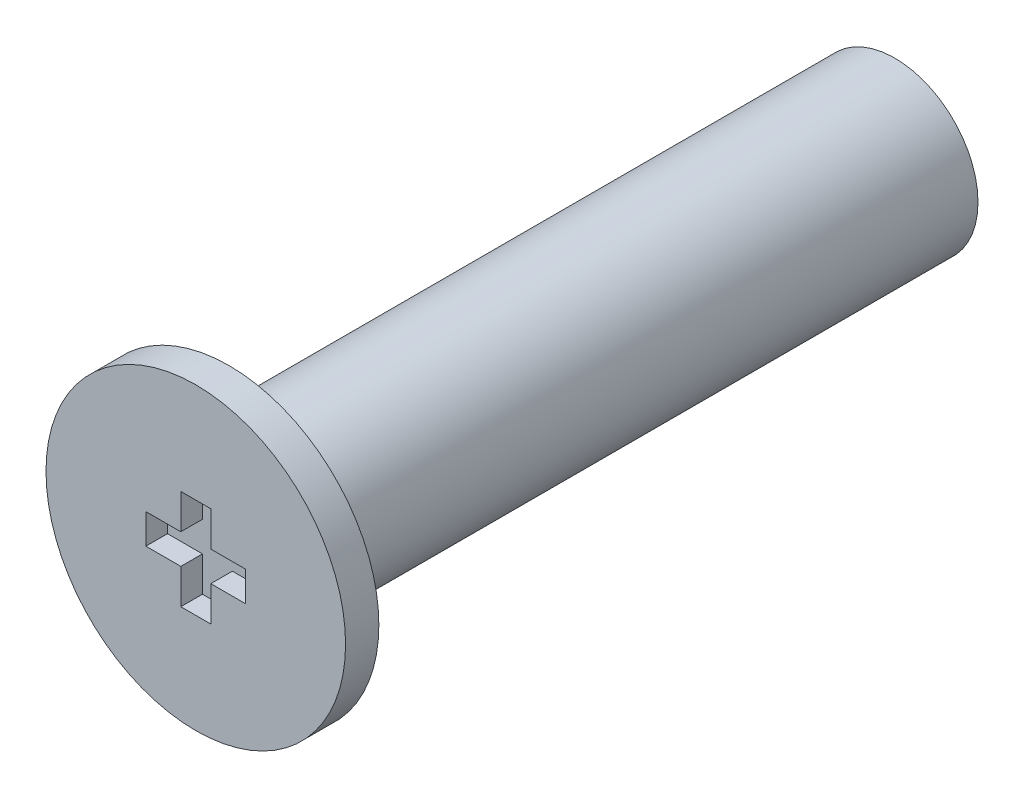
SolidWorks part; units mm, degrees
ref_plane "前视基准面" through (0, 0, 0) normal (0, 0, 1) x (1, 0, 0)
ref_plane "上视基准面" through (0, 0, 0) normal (0, 1, 0) x (1, 0, 0)
ref_plane "右视基准面" through (0, 0, 0) normal (1, 0, 0) x (0, 0, -1)
other "Configuration Table"
sketch "草图1" plane through (0, 0, 0) normal (0, 0, 1) x (1, 0, 0)
  circle A0 centre (0, 0) radius 2.5
extrude "标准杆径_头下长度" add sketch "草图1" against normal blind 20
sketch "草图2" plane through (0, 0, 0) normal (0, 0, 1) x (1, 0, 0)
  circle A0 centre (0, 0) radius 4.25
sketch "草图4" plane through (0, 0, 0) normal (0, 1, 0) x (1, 0, 0)
  line L0 (0, 0) -> (5.9, 0)
  line L1 (5.9, 0) -> (5.9, -0.3477)
  line L2 (0, -3.1) -> (0, 0)
  line L3 (0, 2) -> (0, -5.1) construction
  arc A0 (5.9, -0.3477) -> (0, -3.1) centre (0, 4.6) cw
sketch "草图5" plane through (0, 0, 0) normal (0, 0, 1) x (1, 0, 0)
  line L0 (-0.5, -2.5) -> (0.5, -2.5)
  line L1 (0.5, -2.5) -> (0.5, -0.5)
  line L2 (0.5, -0.5) -> (2.5, -0.5)
  line L3 (2.5, -0.5) -> (2.5, 0.5)
  line L4 (2.5, 0.5) -> (0.5, 0.5)
  line L5 (0.5, 0.5) -> (0.5, 2.5)
  line L6 (0.5, 2.5) -> (-0.5, 2.5)
  line L7 (-0.5, 2.5) -> (-0.5, 0.5)
  line L8 (-0.5, 0.5) -> (-2.5, 0.5)
  line L9 (-2.5, 0.5) -> (-2.5, -0.5)
  line L10 (-2.5, -0.5) -> (-0.5, -0.5)
  line L11 (-0.5, -0.5) -> (-0.5, -2.5)
sketch "草图6" plane through (0, 0, 0) normal (0, 1, 0) x (1, 0, 0)
  line L0 (0, 0) -> (4.5, 0)
  line L1 (4.5, 0) -> (4.5, -1)
  line L2 (4.5, -1) -> (0, -1)
  line L3 (0, -1) -> (0, 0)
  line L4 (0, 2) -> (0, -3) construction
revolve "已确认_十字槽超薄头" add sketch "草图6" angle 360 about L4
sketch "草图7" plane through (0, 0, 0) normal (0, 0, 1) x (1, 0, 0)
  line L0 (-0.45, -1.5) -> (0.45, -1.5)
  line L1 (0.45, -1.5) -> (0.45, -0.45)
  line L2 (0.45, -0.45) -> (1.5, -0.45)
  line L3 (1.5, -0.45) -> (1.5, 0.45)
  line L4 (1.5, 0.45) -> (0.45, 0.45)
  line L5 (0.45, 0.45) -> (0.45, 1.5)
  line L6 (0.45, 1.5) -> (-0.45, 1.5)
  line L7 (-0.45, 1.5) -> (-0.45, 0.45)
  line L8 (-0.45, 0.45) -> (-1.5, 0.45)
  line L9 (-1.5, 0.45) -> (-1.5, -0.45)
  line L10 (-1.5, -0.45) -> (-0.45, -0.45)
  line L11 (-0.45, -0.45) -> (-0.45, -1.5)
extrude "十字槽_PH2_简化" cut sketch "草图7" against normal blind 0.66 from offset 1.01
